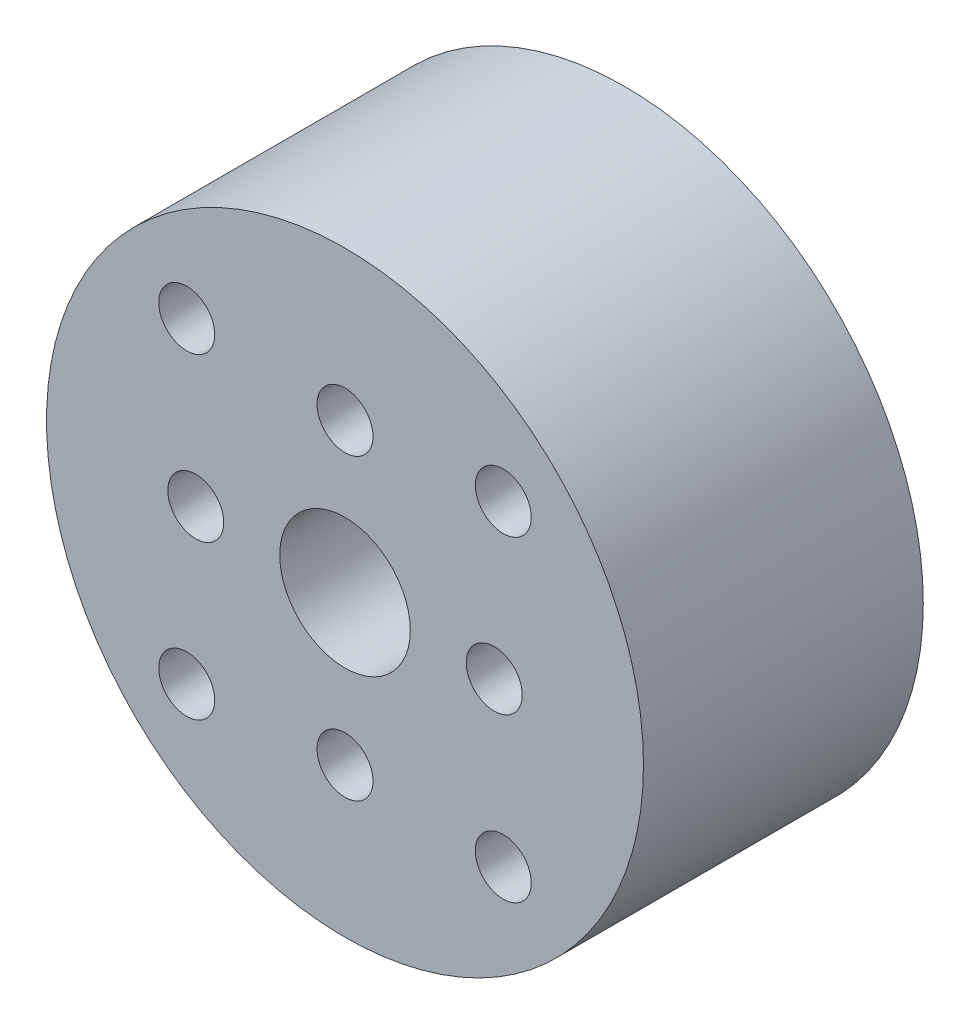
SolidWorks part; units mm, degrees
ref_plane "前视基准面" through (0, 0, 0) normal (0, 0, 1) x (1, 0, 0)
ref_plane "上视基准面" through (0, 0, 0) normal (0, 1, 0) x (1, 0, 0)
ref_plane "右视基准面" through (0, 0, 0) normal (1, 0, 0) x (0, 0, -1)
sketch "草图1" plane through (0, 0, 0) normal (0, 0, 1) x (1, 0, 0)
  line L0 (0, 0) -> (20.0308, 20.0308) construction
  circle A0 centre (0, 0) radius 16
  circle A1 centre (0, 8) radius 1.5
  circle A2 centre (8, 0) radius 1.5
  circle A3 centre (0, -8) radius 1.5
  circle A4 centre (-8, 0) radius 1.5
  circle A5 centre (8.4853, 8.4853) radius 1.5
  circle A6 centre (8.4853, -8.4853) radius 1.5
  circle A7 centre (-8.4853, -8.4853) radius 1.5
  circle A8 centre (-8.4853, 8.4853) radius 1.5
  circle A9 centre (0, 0) radius 3.5
  point P14 (0, 0)
  point P23 (0, 0)
  dimension "D1" = 3
  dimension "D2" = 32
  dimension "D5" = 12
  dimension "D7" = 7
  dimension "D3" = 8
  dimension "D4" = 4
  dimension "D6" = 4
extrude "凸台-拉伸1" add sketch "草图1" along normal blind 15
